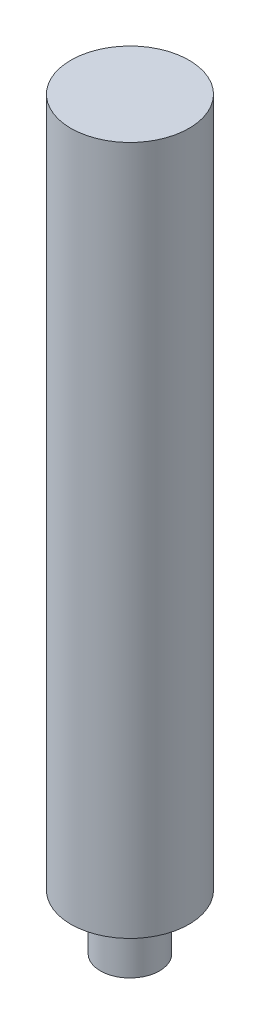
SolidWorks part; units mm, degrees
ref_plane "前基準面" through (0, 0, 0) normal (0, 0, 1) x (1, 0, 0)
ref_plane "上基準面" through (0, 0, 0) normal (0, 1, 0) x (1, 0, 0)
ref_plane "右基準面" through (0, 0, 0) normal (1, 0, 0) x (0, 0, -1)
sketch "草圖1" plane through (0, 0, 0) normal (0, 1, 0) x (1, 0, 0)
  circle A0 centre (0, 0) radius 1.5
extrude "填料-伸長1" add sketch "草圖1" along normal blind 2.8
sketch "草圖2" plane through (0, 2.8, 0) normal (0, 1, 0) x (1, 0, 0)
  circle A0 centre (0, 0) radius 3
extrude "填料-伸長2" add sketch "草圖2" along normal blind 35
